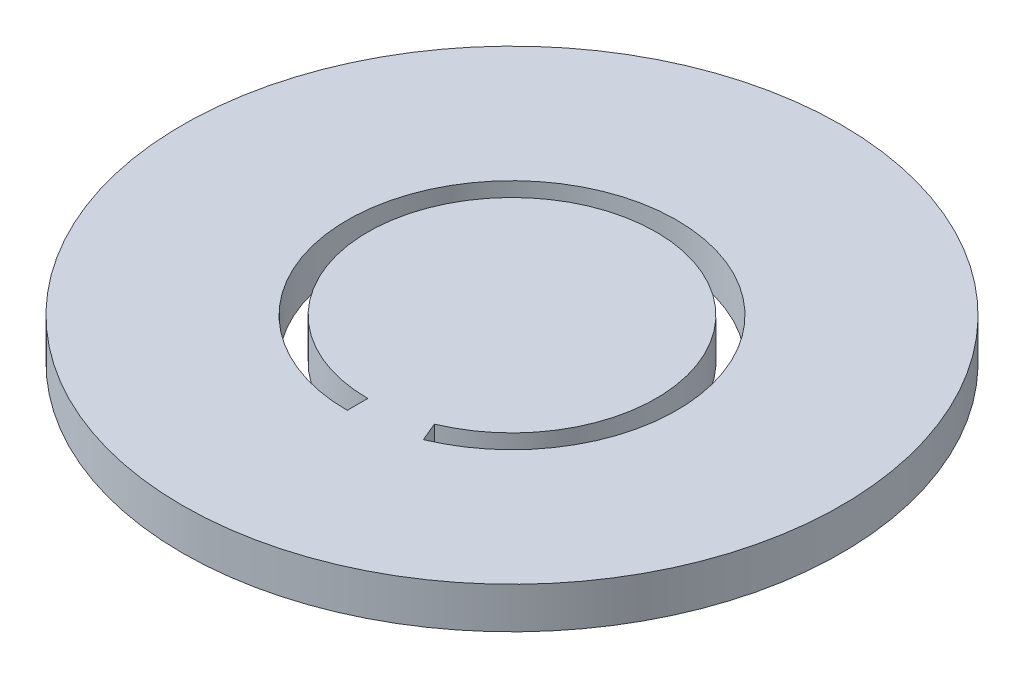
SolidWorks part; units mm, degrees
ref_plane "Front Plane" through (0, 0, 0) normal (0, 0, 1) x (1, 0, 0)
ref_plane "Top Plane" through (0, 0, 0) normal (0, 1, 0) x (1, 0, 0)
ref_plane "Right Plane" through (0, 0, 0) normal (1, 0, 0) x (0, 0, -1)
sketch "Sketch1" plane through (0, 0, 0) normal (0, 1, 0) x (1, 0, 0)
  line L4 (0.6734, -1.6153) -> (0.7696, -1.846)
  line L5 (0, -1.75) -> (0, -2)
  circle A0 centre (0, 0) radius 4
  arc A1 (0.7696, -1.846) -> (0, -2) centre (0, 0) ccw
  arc A2 (0.6734, -1.6153) -> (0, -1.75) centre (0, 0) ccw
extrude "Boss-Extrude1" add sketch "Sketch1" along normal blind 0.5
